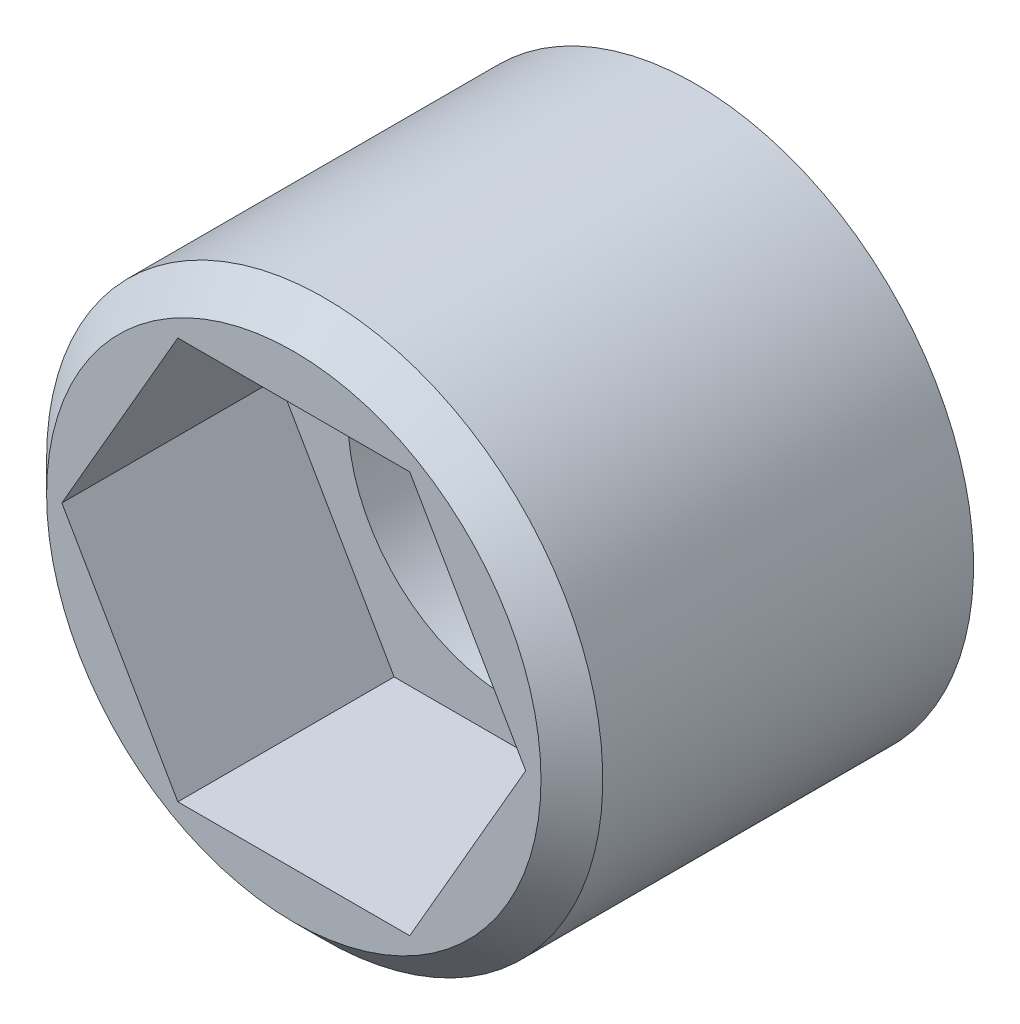
SolidWorks part; units mm, degrees
material "ABS"
ref_plane "Plan de face" through (0, 0, 0) normal (0, 0, 1) x (1, 0, 0)
ref_plane "Plan de dessus" through (0, 0, 0) normal (0, 1, 0) x (1, 0, 0)
ref_plane "Plan de droite" through (0, 0, 0) normal (1, 0, 0) x (0, 0, -1)
sketch "Esquisse1" plane through (0, 0, 0) normal (0, 0, 1) x (1, 0, 0)
  circle A0 centre (0, 0) radius 9
  circle A1 centre (0, 0) radius 5.25
  dimension "D1" = 10.5
  dimension "D2" = 18
extrude "Boss.-Extru.1" add sketch "Esquisse1" along normal blind 13
sketch "Esquisse2" plane through (0, 0, 13) normal (0, 0, 1) x (1, 0, 0)
  line L1 (3.7528, 6.5) -> (-3.7528, 6.5)
  line L2 (-3.7528, 6.5) -> (-7.5056, 0)
  line L3 (-7.5056, 0) -> (-3.7528, -6.5)
  line L4 (-3.7528, -6.5) -> (3.7528, -6.5)
  line L5 (3.7528, -6.5) -> (7.5056, 0)
  line L6 (7.5056, 0) -> (3.7528, 6.5)
  circle A0 centre (0, 0) radius 6.5 construction
  dimension "D1" = 13
extrude "Enlèv. mat.-Extru.1" cut sketch "Esquisse2" against normal blind 7
chamfer "Chanfrein1" distance 1 angle 45 1 edges at (9, 0, 13)
